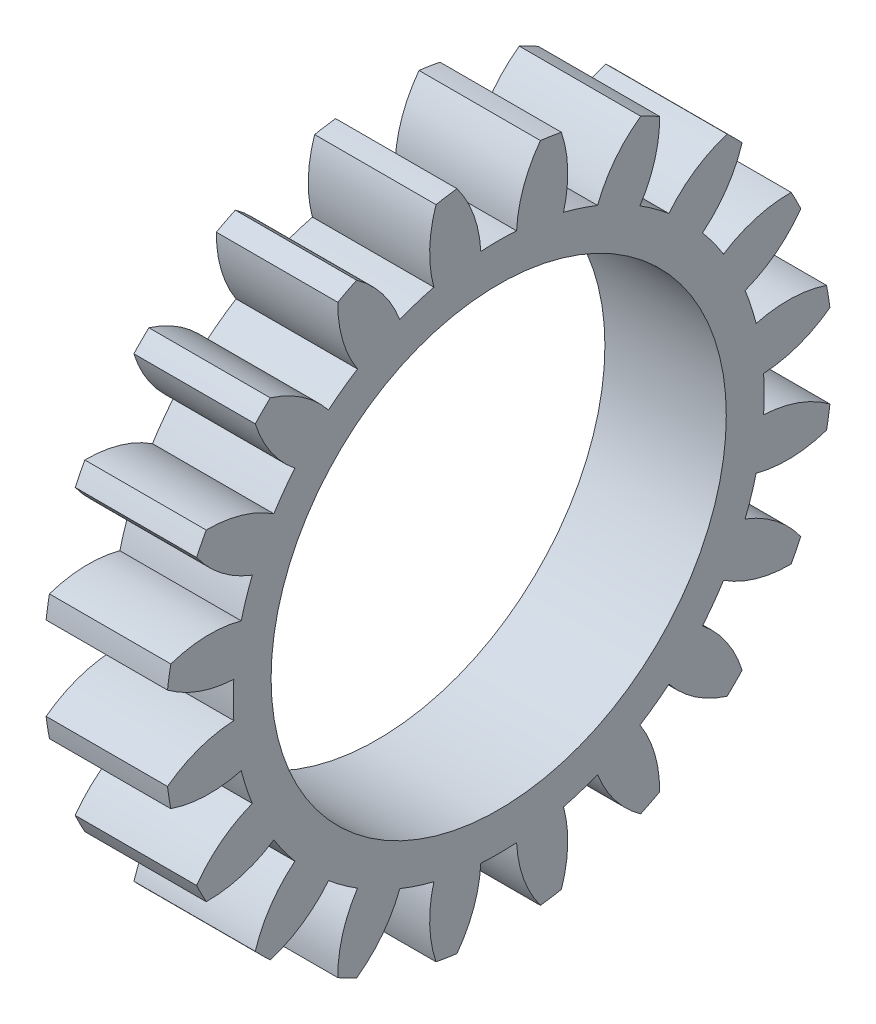
SolidWorks part; units mm, degrees
ref_plane "Plane1" through (0, 0, 0) normal (0, 0, 1) x (1, 0, 0)
ref_plane "Plane2" through (0, 0, 0) normal (0, 1, 0) x (1, 0, 0)
ref_plane "Plane3" through (0, 0, 0) normal (1, 0, 0) x (0, 0, -1)
other "Configuration Table"
sketch "HoldingSke" plane through (0, 0, 0) normal (0, 1, 0) x (1, 0, 0)
  line L0 (0, 0) -> (0.9397, -0.342)
  line L1 (-15, 0) -> (100, 0) construction
  line L2 (0, 0) -> (-2.1039, 2.3779)
  line L3 (0, 0) -> (-11.863, 4.5341)
  line L4 (0, 0) -> (8.1152, 2.9537)
  line L5 (0, 0) -> (-46.8476, -17.4728)
  line L6 (0, 0) -> (-3.3159, -2.2372)
  line L7 (-2.1039, 2.3779) -> (8.6586, 51.2059)
  line L8 (-76.2, 54.61) -> (-73.9, 54.61)
  line L9 (-67.7845, 28.3722) -> (-49.3413, 33.142)
  line L10 (-76.2, 71.12) -> (104.1128, 71.12)
  line L11 (0, 0) -> (-4, 0)
  line L12 (-76.2, 101.6) -> (-76.162, 101.6)
  line L13 (24.9733, 27.94) -> (52.9518, 28.4284)
  line L14 (24.9733, 27.94) -> (24.9743, 27.94)
  line L15 (24.9733, 27.94) -> (100.4006, 29.5858)
  line L16 (-63.627, -1) -> (-12.827, -1)
  circle A0 centre (0, 0) radius 7.5
  circle A1 centre (0, 0) radius 8.749
  circle A2 centre (0, 0) radius 37.5
  circle A3 centre (0, 0) radius 7.5
  dimension "MHD" = 17.498
  dimension "Hub_dia" = 75
  dimension "Bore" = 15
  dimension "MBD" = 15
  dimension "Num_teeth" = 20
  dimension "Pitch" = 1
  dimension "Overall_len" = 50
  dimension "Show_teeth" = 20
  dimension "Thickness" = 4
  dimension "OAL" = 50.0001
  dimension "T_dim" = 2.3
  dimension "Ap" = 14.5
  dimension "H" = 19.05
  dimension "Pitch_radius" = 180.3128
  dimension "Width" = 4
  dimension "Backlash" = 0.038
  dimension "Addendum_fac" = 1
  dimension "Dedendum_fac" = 1.25
  dimension "Clearance_fac" = 0.25
  dimension "Dedendum_add" = 0.001
  dimension "Module" = 1
sketch "BasProSke" plane through (0, 0, 0) normal (0, 1, 0) x (1, 0, 0)
  line L0 (-10, 0) -> (60, 0) construction
  line L1 (0, 0) -> (0, 11)
  line L2 (0, 0) -> (4, 0)
  line L3 (4, 0) -> (4, 11)
  line L4 (4, 11) -> (0, 11)
  dimension "Thickness" = 4
  dimension "Diameter" = 22
revolve "Base-Revolve" add sketch "BasProSke" angle 360 about L0
sketch "TooCutSke" plane through (0, 0, 0) normal (1, 0, 0) x (0, 0, -1)
  line L1 (0, 0) -> (0, 107) construction
  line L2 (0, 0) -> (-0.8511, 9.9637) construction
  line L3 (0, 0) -> (-3.1206, 19.7028) construction
  line L4 (-0.8511, 9.9637) -> (-1.5603, 9.8514) construction
  arc A0 (0.5894, 8.7291) -> (-0.5894, 8.7291) centre (0, 0) ccw
  arc A1 (1.3917, 10.9372) -> (-1.3917, 10.9372) centre (0, 0) ccw
  circle A2 centre (0, 0) radius 10 construction
  circle A3 centre (0, 0) radius 9.6815 construction
  arc A4 (-0.5894, 8.7291) -> (-1.3917, 10.9372) centre (-4.5843, 8.5273) ccw
  arc A5 (1.3917, 10.9372) -> (0.5894, 8.7291) centre (4.5843, 8.5273) ccw
  dimension "Root_dia" = 17.498
  dimension "Overcut_dia" = 22.0508
  dimension "Pitch_dia" = 20
  dimension "Base_dia" = 19.363
  dimension "Flank_rad" = 4
  dimension "Half_ang" = 9
  dimension "Half_CT" = 0.7181
extrude "ToothCut" cut sketch "TooCutSke" along normal through all
fillet "Breaks" [suppressed] radius 0.02
fillet "RootFillets" [suppressed] radius 0.251
pattern_circular "TeethCuts" count 20 every 18 about axis through (-10, 0, 0) along (1, 0, 0) of "ToothCut", "RootFillets", "Breaks"
sketch "HubNeaOneSke" plane through (0, 0, 0) normal (-1, 0, 0) x (0, 0, 1)
  circle A0 centre (0, 0) radius 8.749
  dimension "Diameter" = 17.498
extrude "HubNearOne" [suppressed] add sketch "HubNeaOneSke" along normal blind 46.0001
sketch "HubNeaBotSke" plane through (0, 0, 0) normal (-1, 0, 0) x (0, 0, 1)
  circle A0 centre (0, 0) radius 8.749
  dimension "Diameter" = 17.498
extrude "HubNearBoth" [suppressed] add sketch "HubNeaBotSke" along normal blind 23
ref_plane "FarPln" through (4, 0, 0) normal (1, 0, 0) x (0, 0, -1)
sketch "HubFarSke" plane through (4, 0, 0) normal (1, 0, 0) x (0, 0, -1)
  circle A0 centre (0, 0) radius 8.749
  dimension "Diameter" = 17.498
extrude "HubFar" [suppressed] add sketch "HubFarSke" along normal blind 23
sketch "BorSke" plane through (0, 0, 0) normal (1, 0, 0) x (0, 0, -1)
  circle A0 centre (0, 0) radius 7.5
  dimension "Diameter" = 15
extrude "Bore" cut sketch "BorSke" along normal mid plane 100.0001
sketch "KeySke" plane through (0, 0, 0) normal (1, 0, 0) x (0, 0, -1)
  line L0 (-2.5, 0) -> (-2.5, 9.8)
  line L1 (-2.5, 9.8) -> (2.5, 9.8)
  line L2 (2.5, 9.8) -> (2.5, 0)
  line L3 (0, 0) -> (0, 34) construction
  line L4 (-2.5, 0) -> (2.5, 0)
  dimension "Offset" = 9.8
  dimension "Width" = 5
extrude "Keyway" [suppressed] cut sketch "KeySke" along normal mid plane 100.0001
pattern_circular "Keyway2" [suppressed] count 2 every 90 about axis through (-10, 0, 0) along (1, 0, 0)
equation "' \"Module@HoldingSke\" = 6.35"
equation "' \"Num_teeth@HoldingSke\" = 12"
equation "' \"Ap@HoldingSke\" =  20"
equation "' \"Ap@HoldingSke\" = 20"
equation "' \"Width@HoldingSke\" = 0.5 * 25.4"
equation "' \"Hub_dia@HoldingSke\"= 1 * 25.4"
equation "' \"Hub_dia@HoldingSke\" = 1 * 25.4"
equation "' \"Overall_len@HoldingSke\" = 1.0 * 25.4"
equation "' \"Bore@HoldingSke\" = 0.75 * 25.4"
equation "' \"T_dim@HoldingSke\" = 0.1 * 25.4"
equation "' \"Width@KeySke\" = 0.25 * 25.4"
equation "' \"Show_teeth@HoldingSke\" = 13"
equation "' \"Backlash@HoldingSke\" = 0.009 * 25.4"
equation "' \"Addendum_fac@HoldingSke\" = 1.0"
equation "' \"Dedendum_fac@HoldingSke\" = 1.25"
equation "' \"Dedendum_add@HoldingSke\" = 0.00005 * 25.4"
equation "' \"Clearance_fac@HoldingSke\" = 0.25"
equation "\"Pitch@HoldingSke\" = 1 / \"Module@HoldingSke\""
equation "\"Overcut_dia@TooCutSke\" = (\"Num_teeth@HoldingSke\" + 2 * \"Addendum_fac@HoldingSke\") / \"Pitch@HoldingSke\" + 0.002 * 25.4"
equation "\"Pitch_dia@TooCutSke\" = \"Num_teeth@HoldingSke\" / \"Pitch@HoldingSke\""
equation "\"Base_dia@TooCutSke\" = \"Num_teeth@HoldingSke\" / \"Pitch@HoldingSke\" * cos((\"Ap@HoldingSke\"  * 3.14159265 / 180))"
equation "\"Root_dia@TooCutSke\" = (\"Num_teeth@HoldingSke\" + 2) / \"Pitch@HoldingSke\" - 2 * (\"Addendum_fac@HoldingSke\" + \"Dedendum_fac@HoldingSke\") / \"Pitch@HoldingSke\" - \"Dedendum_add@HoldingSke\" * 2"
equation "\"Half_ang@TooCutSke\" = 180 / \"Num_teeth@HoldingSke\""
equation "\"Half_CT@TooCutSke\" = \"Num_teeth@HoldingSke\" / \"Pitch@HoldingSke\" * sin((3.14159265 / 2 / \"Num_teeth@HoldingSke\")) / 2 - 7 * \"Backlash@HoldingSke\" / 4"
equation "\"Flank_rad@TooCutSke\" = \"Num_teeth@HoldingSke\" / \"Pitch@HoldingSke\" / 5"
equation "\"Radius@RootFillets\" = \"Clearance_fac@HoldingSke\" / \"Pitch@HoldingSke\" + \"Dedendum_add@HoldingSke\""
equation "\"Break_rad@Breaks\" = 0.02 / \"Pitch@HoldingSke\""
equation "\"Thickness@HoldingSke\" = \"Width@HoldingSke\""
equation "\"OAL@HoldingSke\" = \"Thickness@HoldingSke\""
equation "\"MHD@HoldingSke\" = (\"Num_teeth@HoldingSke\" + 2) / \"Pitch@HoldingSke\" - 2 * (\"Addendum_fac@HoldingSke\" + \"Dedendum_fac@HoldingSke\")  / \"Pitch@HoldingSke\" - \"Dedendum_add@HoldingSke\" * 2"
equation "\"MBD@HoldingSke\" = (\"Num_teeth@HoldingSke\" + 2) / \"Pitch@HoldingSke\" - 2 * (\"Addendum_fac@HoldingSke\" + \"Dedendum_fac@HoldingSke\")  / \"Pitch@HoldingSke\" - \"Dedendum_add@HoldingSke\" * 2 - 0.002 * 25.4"
equation "\"MHD@HoldingSke\" = ((sgn( \"MHD@HoldingSke\" - \"Hub_dia@HoldingSke\" )-1)*( \"MHD@HoldingSke\" - \"Hub_dia@HoldingSke\" ))/-2+ \"Hub_dia@HoldingSke\""
equation "\"MBD@HoldingSke\" = ((sgn( \"MBD@HoldingSke\" - \"Bore@HoldingSke\" )-1)*( \"MBD@HoldingSke\" - \"Bore@HoldingSke\" ))/-2+ \"Bore@HoldingSke\""
equation "\"OAL@HoldingSke\" = ((sgn( \"OAL@HoldingSke\" - \"Overall_len@HoldingSke\" )+1)*( \"OAL@HoldingSke\" - \"Overall_len@HoldingSke\" ))/2 + \"Overall_len@HoldingSke\" + 0.000002 * 25.4"
equation "\"Num_teeth@TeethCuts\" = int( \"Show_teeth@HoldingSke\" ) + 1"
equation "\"Num_teeth@TeethCuts\" = ((sgn( \"Num_teeth@TeethCuts\" - \"Num_teeth@HoldingSke\" )-1)*( \"Num_teeth@TeethCuts\" - \"Num_teeth@HoldingSke\" ))/-2+ \"Num_teeth@HoldingSke\""
equation "\"Num_teeth@TeethCuts\" = ((sgn( \"Num_teeth@TeethCuts\" - 2.0)+1)*( \"Num_teeth@TeethCuts\" - 2.0))/2 +2.0"
equation "\"Angle@TeethCuts\" = 360.0 / \"Num_teeth@HoldingSke\""
equation "\"Diameter@BasProSke\" = (\"Num_teeth@HoldingSke\" + 2 * \"Addendum_fac@HoldingSke\") / \"Pitch@HoldingSke\""
equation "\"Thickness@BasProSke\"  = \"Thickness@HoldingSke\""
equation "' \"Fillet_rad@BasProSke\" =  \"Thickness@HoldingSke\" * 0.05"
equation "' \"Fillet_rad@BasProSke\" = \"Thickness@HoldingSke\" * 0.05"
equation "\"MHD@HoldingSke\" = ((sgn( \"MHD@HoldingSke\" - \"Root_dia@TooCutSke\" )-1)*( \"MHD@HoldingSke\" - \"Root_dia@TooCutSke\" ))/-2+ \"Root_dia@TooCutSke\""
equation "\"Diameter@HubNeaOneSke\" = \"MHD@HoldingSke\""
equation "\"Length@HubNearOne\" = \"OAL@HoldingSke\" - \"Thickness@BasProSke\""
equation "\"Diameter@HubNeaBotSke\" = \"MHD@HoldingSke\""
equation "\"Length@HubNearBoth\" = ( \"OAL@HoldingSke\" - \"Thickness@BasProSke\" ) / 2.0"
equation "\"Thickness@FarPln\" = \"Thickness@BasProSke\""
equation "\"Diameter@HubFarSke\" = \"MHD@HoldingSke\""
equation "\"Length@HubFar\" = ( \"OAL@HoldingSke\" - \"Thickness@BasProSke\" ) / 2.0"
equation "\"Diameter@BorSke\" = \"MBD@HoldingSke\""
equation "\"D1@Bore\" = \"OAL@HoldingSke\" * 2.0"
equation "\"D1@Keyway\" = \"OAL@HoldingSke\" * 2.0"
equation "\"Offset@KeySke\" = \"T_dim@HoldingSke\" + \"MBD@HoldingSke\" / 2.0"
